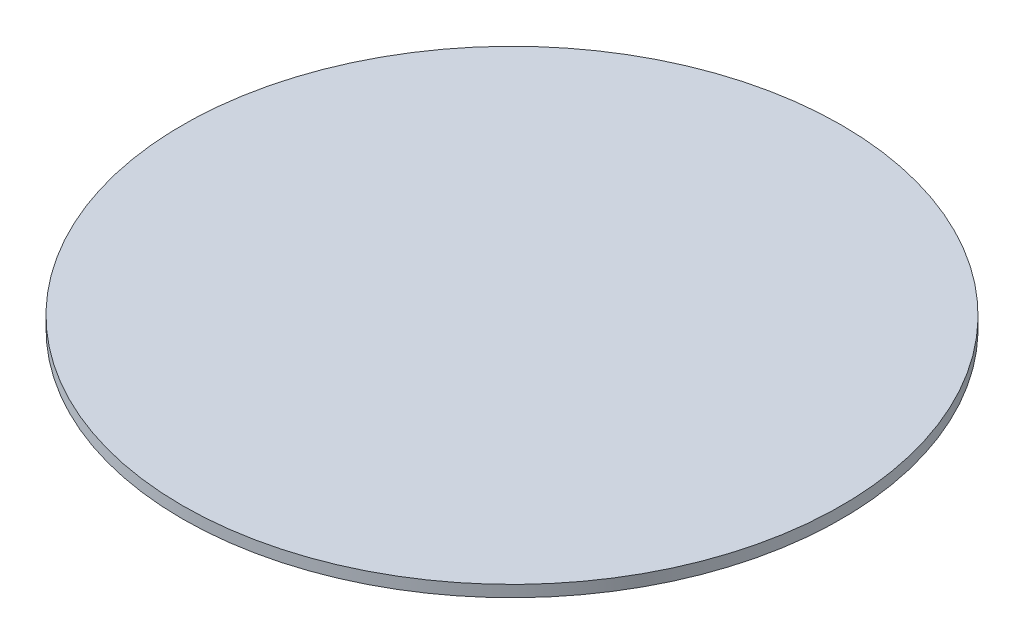
SolidWorks part; units mm, degrees
ref_plane "Front Plane" through (0, 0, 0) normal (0, 0, 1) x (1, 0, 0)
ref_plane "Top Plane" through (0, 0, 0) normal (0, 1, 0) x (1, 0, 0)
ref_plane "Right Plane" through (0, 0, 0) normal (1, 0, 0) x (0, 0, -1)
sketch "Sketch1" plane through (0, 0, 0) normal (0, 1, 0) x (1, 0, 0)
  line L0 (0, 0) -> (-200, 0) construction
  line L1 (0, 0) -> (100, 173.2051) construction
  line L2 (0, 0) -> (100, -173.2051) construction
  circle A0 centre (0, 0) radius 200
  circle A1 centre (-156, -40) radius 7 construction
  circle A2 centre (-156, 40) radius 7
  circle A3 centre (43.359, 155.1) radius 7 construction
  circle A4 centre (112.641, 115.1) radius 7
  circle A5 centre (112.641, -115.1) radius 7 construction
  circle A6 centre (43.359, -155.1) radius 7
  dimension "D1" = 80
  dimension "D3" = 14
  dimension "D2" = 156
  dimension "D4" = 400
  dimension "D5" = 3
extrude "Boss-Extrude1" add sketch "Sketch1" along normal blind 7 contours A0
